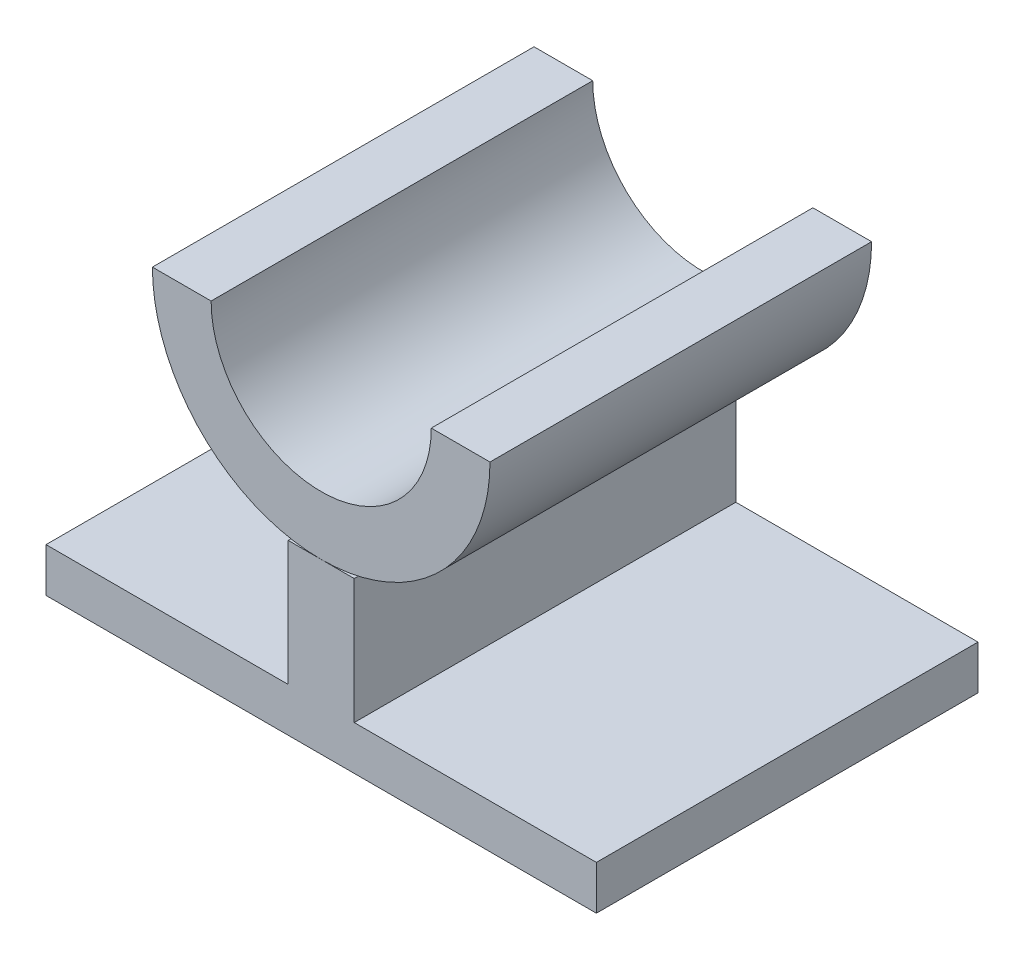
SolidWorks part; units mm, degrees
ref_plane "Front Plane" through (0, 0, 0) normal (0, 0, 1) x (1, 0, 0)
ref_plane "Top Plane" through (0, 0, 0) normal (0, 1, 0) x (1, 0, 0)
ref_plane "Right Plane" through (0, 0, 0) normal (1, 0, 0) x (0, 0, -1)
sketch "Sketch1" plane through (0, 0, 0) normal (0, 1, 0) x (1, 0, 0)
  line L0 (0, 26) -> (0.0001, 26) construction
  line L1 (37.5, -26) -> (-37.5, -26)
  line L2 (37.5, -26) -> (37.5, 26)
  line L3 (37.5, 26) -> (-37.5, 26)
  line L4 (-37.5, -26) -> (-37.5, 26)
  line L5 (37.5, -26) -> (-37.5, 26) construction
  line L6 (37.5, 26) -> (-37.5, -26) construction
  line L7 (0.0001, 26) -> (0, -26) construction
  point P0 (0, 0)
  dimension "D1" = 52
  dimension "D2" = 75
extrude "Boss-Extrude1" add sketch "Sketch1" along normal blind 6
sketch "Sketch2" plane through (0, 6, 0) normal (0, 1, 0) x (1, 0, 0)
  line L0 (0, 26) -> (0, -26) construction
  line L1 (37.5, 26) -> (-37.5, 26) construction
  line L2 (-37.5, -26) -> (37.5, -26) construction
  line L4 (4.5, 26) -> (-4.5, 26)
  line L5 (4.5, 26) -> (4.5, -26)
  line L6 (4.5, -26) -> (-4.5, -26)
  line L7 (-4.5, 26) -> (-4.5, -26)
  line L8 (4.5, 26) -> (-4.5, -26) construction
  line L9 (4.5, -26) -> (-4.5, 26) construction
  point P6 (0, 0)
  dimension "D1" = 9
extrude "Boss-Extrude2" add sketch "Sketch2" along normal blind 17
sketch "Sketch3" plane through (0, 0, 26) normal (0, 0, 1) x (1, 0, 0)
  line L0 (-23, 46) -> (-15, 46)
  line L1 (15, 46) -> (23, 46)
  arc A0 (-23, 46) -> (23, 46) centre (0, 46) ccw
  arc A1 (-15, 46) -> (15, 46) centre (0, 46) ccw
  dimension "D2" = 23
  dimension "D3" = 15
  dimension "D1" = 46
extrude "Boss-Extrude3" add sketch "Sketch3" against normal blind 52 separate body
ref_plane "Plane1" through (-4.5, 23, -26) normal (0, -1, 0) x (-1, 0, 0)
sketch "Sketch6" plane through (0, 0, -26) normal (0, 0, -1) x (-1, 0, 0)
  line L1 (63.7162, 10.6295) -> (61.0482, 13.2975)
